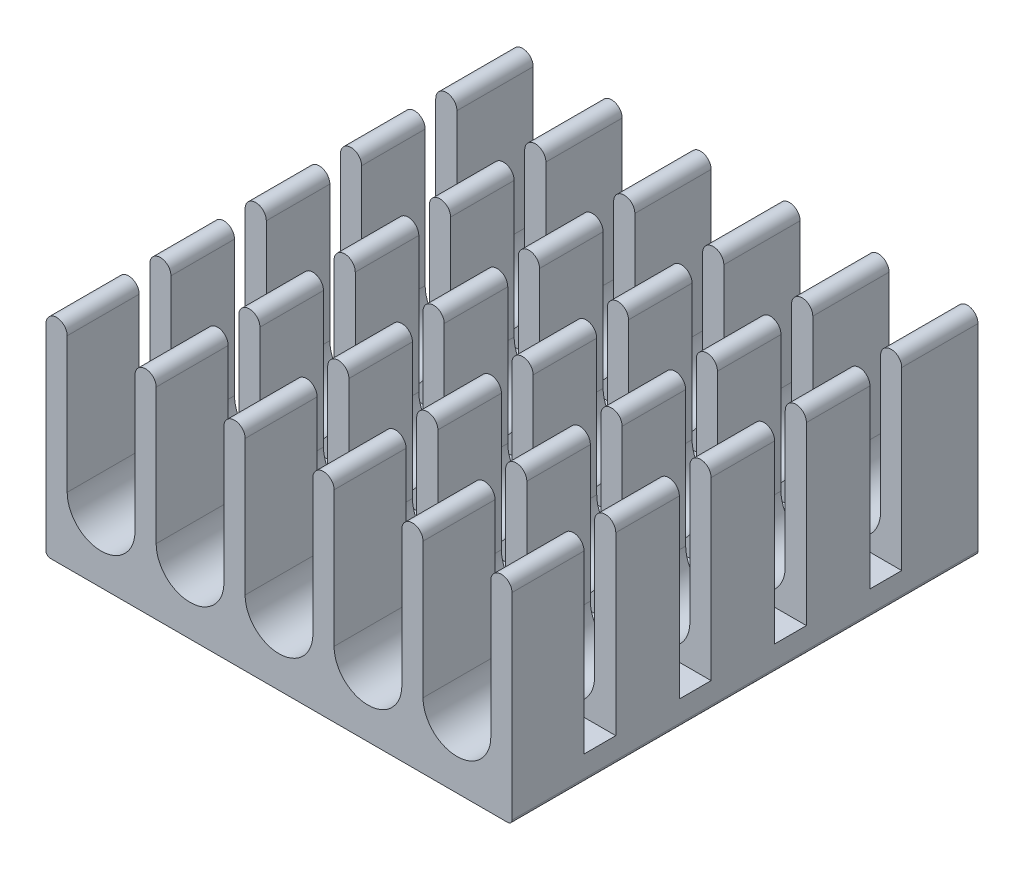
SolidWorks part; units mm, degrees
ref_plane "Front Plane" through (0, 0, 0) normal (0, 0, 1) x (1, 0, 0)
ref_plane "Top Plane" through (0, 0, 0) normal (0, 1, 0) x (1, 0, 0)
ref_plane "Right Plane" through (0, 0, 0) normal (1, 0, 0) x (0, 0, -1)
sketch "草图1" plane through (0, 0, 0) normal (0, 1, 0) x (1, 0, 0)
  line L0 (27.1847, 0) -> (49.1847, 0)
  line L1 (49.1847, 0) -> (49.1847, 22)
  line L2 (49.1847, 22) -> (27.1847, 22)
  line L3 (27.1847, 22) -> (27.1847, 0)
extrude "凸台-拉伸1" add sketch "草图1" along normal blind 10
sketch "草图2" plane through (27.1847, 0, 0) normal (-1, 0, 0) x (0, 0, 1)
  line L0 (-18.4, 10) -> (-16.9, 10)
  line L2 (-22, 10) -> (0, 10) construction
  line L3 (-3.4, 10) -> (-3.4, 1.7)
  line L5 (-4.9, 1.7) -> (-4.9, 10)
  line L6 (-13.9, 10) -> (-12.4, 10)
  line L7 (-7.9, 10) -> (-7.9, 1.7)
  line L9 (-9.4, 1.7) -> (-9.4, 10)
  line L10 (-9.4, 10) -> (-7.9, 10)
  line L11 (-12.4, 10) -> (-12.4, 1.7)
  line L13 (-13.9, 1.7) -> (-13.9, 10)
  line L14 (-4.9, 10) -> (-3.4, 10)
  line L15 (-16.9, 10) -> (-16.9, 1.7)
  line L17 (-18.4, 1.7) -> (-18.4, 10)
  line L18 (-13.9, 1.7) -> (-13.9, 1.2)
  line L19 (-17.65, 1.2) -> (-18.4, 1.2)
  line L20 (-18.4, 1.2) -> (-18.4, 1.7)
  line L21 (-16.9, 1.7) -> (-16.9, 1.2)
  line L22 (-16.9, 1.2) -> (-17.65, 1.2)
  line L23 (-13.9, 1.2) -> (-12.4, 1.2)
  line L24 (-12.4, 1.2) -> (-12.4, 1.7)
  line L25 (-9.4, 1.7) -> (-9.4, 1.2)
  line L26 (-9.4, 1.2) -> (-7.9, 1.2)
  line L27 (-7.9, 1.2) -> (-7.9, 1.7)
  line L28 (-4.9, 1.7) -> (-4.9, 1.2)
  line L29 (-4.9, 1.2) -> (-3.4, 1.2)
  line L30 (-3.4, 1.2) -> (-3.4, 1.7)
extrude "切除-拉伸1" cut sketch "草图2" against normal through all
sketch "草图3" plane through (0, 0, 0) normal (0, 0, 1) x (1, 0, 0)
  line L0 (43.9847, 3.1) -> (43.9847, 10)
  line L1 (27.1847, 10) -> (49.1847, 10) construction
  line L3 (39.7847, 3.1) -> (39.7847, 10)
  line L4 (39.7847, 10) -> (36.5847, 10)
  line L5 (36.5847, 10) -> (36.5847, 3.1)
  line L7 (43.9847, 10) -> (40.7847, 10)
  line L8 (40.7847, 10) -> (40.7847, 3.1)
  line L9 (48.1847, 3.1) -> (48.1847, 10)
  line L10 (48.1847, 10) -> (44.9847, 10)
  line L11 (44.9847, 10) -> (44.9847, 3.1)
  line L12 (35.5847, 3.1) -> (35.5847, 10)
  line L13 (35.5847, 10) -> (32.3847, 10)
  line L14 (32.3847, 10) -> (32.3847, 3.1)
  line L15 (31.3847, 3.1) -> (31.3847, 10)
  line L16 (31.3847, 10) -> (28.1847, 10)
  line L17 (28.1847, 10) -> (28.1847, 3.1)
  arc A0 (39.7847, 3.1) -> (36.5847, 3.1) centre (38.1847, 3.1) cw
  arc A1 (43.9847, 3.1) -> (40.7847, 3.1) centre (42.3847, 3.1) cw
  arc A2 (48.1847, 3.1) -> (44.9847, 3.1) centre (46.5847, 3.1) cw
  arc A3 (35.5847, 3.1) -> (32.3847, 3.1) centre (33.9847, 3.1) cw
  arc A4 (31.3847, 3.1) -> (28.1847, 3.1) centre (29.7847, 3.1) cw
  dimension "D1" = 3
  dimension "D2" = 3
extrude "切除-拉伸2" cut sketch "草图3" against normal through all
sketch "草图4" plane through (0, 0, 0) normal (0, 0, 1) x (1, 0, 0)
  line L0 (31.3847, 9.5) -> (31.3847, 10)
  line L2 (36.5847, 10) -> (36.5847, 3.1) construction
  line L3 (35.5847, 3.1) -> (35.5847, 10) construction
  line L4 (35.5847, 9.5) -> (35.5847, 10)
  line L5 (35.5847, 10) -> (36.5847, 10)
  line L6 (36.5847, 10) -> (36.5847, 9.5)
  line L7 (32.3847, 10) -> (32.3847, 9.5)
  line L8 (31.3847, 10) -> (32.3847, 10)
  line L9 (27.1847, 9.5) -> (27.1847, 10)
  line L10 (28.1847, 10) -> (28.1847, 9.5)
  line L11 (27.1847, 10) -> (28.1847, 10)
  line L12 (39.7847, 9.5) -> (39.7847, 10)
  line L13 (40.7847, 10) -> (40.7847, 9.5)
  line L14 (39.7847, 10) -> (40.7847, 10)
  line L15 (43.9847, 9.5) -> (43.9847, 10)
  line L16 (44.9847, 10) -> (44.9847, 9.5)
  line L17 (43.9847, 10) -> (44.9847, 10)
  line L18 (48.1847, 9.5) -> (48.1847, 10)
  line L19 (48.1847, 10) -> (49.1847, 10)
  line L20 (49.1847, 10) -> (49.1847, 9.5)
  arc A0 (36.5847, 9.5) -> (35.5847, 9.5) centre (36.0847, 9.5) ccw
  arc A1 (32.3847, 9.5) -> (31.3847, 9.5) centre (31.8847, 9.5) ccw
  arc A2 (28.1847, 9.5) -> (27.1847, 9.5) centre (27.6847, 9.5) ccw
  arc A3 (40.7847, 9.5) -> (39.7847, 9.5) centre (40.2847, 9.5) ccw
  arc A4 (44.9847, 9.5) -> (43.9847, 9.5) centre (44.4847, 9.5) ccw
  arc A5 (49.1847, 9.5) -> (48.1847, 9.5) centre (48.6847, 9.5) ccw
  line M2 (28.1847, 3.1) -> (28.1847, 10)
  line M3 (28.1847, 10) -> (27.1847, 10)
  line M4 (27.1847, 10) -> (27.1847, 0)
  line M6 (49.1847, 0) -> (49.1847, 10)
  line M7 (49.1847, 10) -> (48.1847, 10)
  line M8 (48.1847, 10) -> (48.1847, 3.1)
  line M10 (44.9847, 3.1) -> (44.9847, 10)
  line M11 (44.9847, 10) -> (43.9847, 10)
  line M12 (43.9847, 10) -> (43.9847, 3.1)
  line M14 (40.7847, 3.1) -> (40.7847, 10)
  line M15 (40.7847, 10) -> (39.7847, 10)
  line M16 (39.7847, 10) -> (39.7847, 3.1)
  line M18 (36.5847, 3.1) -> (36.5847, 10)
  line M19 (36.5847, 10) -> (35.5847, 10)
  line M20 (35.5847, 10) -> (35.5847, 3.1)
  line M22 (32.3847, 3.1) -> (32.3847, 10)
  line M23 (32.3847, 10) -> (31.3847, 10)
  line M24 (31.3847, 10) -> (31.3847, 3.1)
extrude "切除-拉伸4" cut sketch "草图4" against normal through all contours A5 M6 M7 | A5 L19 M8 | A4 M10 M11 | A4 L17 M12 | A3 M14 M15 | A3 L14 M16 | A0 M18 M19 | A0 L5 M20 | A1 M22 M23 | A1 L8 M24 | A2 M2 M3 | A2 L11 M4
fillet "圆角1" radius 0.2 2 edges at (49.1847, 0, -11) (27.1847, 0, -11)
